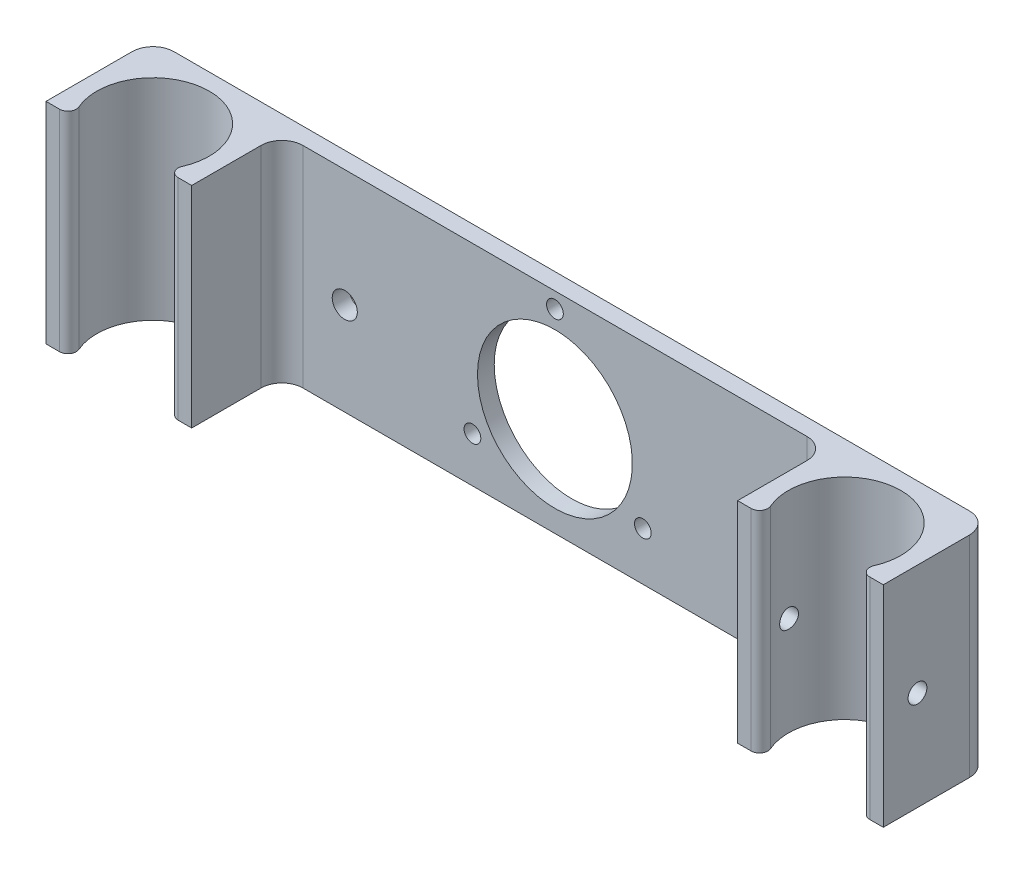
SolidWorks part; units mm, degrees
ref_plane "Front Plane" through (0, 0, 0) normal (0, 0, 1) x (1, 0, 0)
ref_plane "Top Plane" through (0, 0, 0) normal (0, 1, 0) x (1, 0, 0)
ref_plane "Right Plane" through (0, 0, 0) normal (1, 0, 0) x (0, 0, -1)
sketch "Sketch1" plane through (0, 0, 0) normal (0, 1, 0) x (1, 0, 0)
  line L1 (-17.4, 17.4) -> (17.4, 17.4)
  line L2 (-17.4, 13.4) -> (-17.4, -17.4)
  line L3 (-17.4, -17.4) -> (17.4, -17.4)
  line L4 (17.4, 17.4) -> (17.4, -17.4)
  line L5 (0, -17.4) -> (0, 17.4) construction
  line L6 (-17.4, 0) -> (17.4, 0) construction
  line L7 (-17.4, 17.4) -> (-82.6, 17.4)
  line L9 (-17.4, 13.4) -> (-82.6, 13.4)
  line L10 (-82.6, 17.4) -> (-82.6, 13.4)
  circle A0 centre (0, 0) radius 13.45
  dimension "D1" = 26.9
  dimension "D2" = 34.8
  dimension "D3" = 34.8
  dimension "D4" = 65.2
  dimension "D5" = 4
extrude "Boss-Extrude2" add sketch "Sketch1" along normal blind 52 and the other way blind 1
mirror "Mirror2" about plane through (-82.6, -1, -17.4) normal (-1, 0, 0) of "Boss-Extrude2"
fillet "Fillet1" radius 3 4 edges at (17.4, 25.5, 17.4) (-17.4, 25.5, 17.4) (-182.6, 25.5, 17.4) (-147.8, 25.5, 17.4)
fillet "Fillet2" radius 5 4 edges at (17.4, 25.5, -17.4) (-17.4, 25.5, -13.4) (-182.6, 25.5, -17.4) (-147.8, 25.5, -13.4)
sketch "Sketch9" plane through (-17.4, 0, 0) normal (-1, 0, 0) x (0, 0, 1)
  line L0 (-13.45, -1) -> (13.45, -1) construction
  line L1 (-13.45, -1) -> (13.45, -1) construction
  line L3 (14.4, -1) -> (14.4, 52) construction
  line L4 (14.4, -1) -> (14.4, 52) construction
  circle A0 centre (0, 25.5) radius 2.25
  point P5 (0, -1)
  point P9 (14.4, 25.5)
  dimension "D1" = 4.5
extrude "Cut-Extrude2" cut sketch "Sketch9" against normal through all
ref_plane "Plane2" through (-82.6, 0, 0) normal (1, 0, 0) x (0, 0, -1)
sketch "Sketch11" plane through (0, -1, 0) normal (0, -1, 0) x (1, 0, 0)
  line L1 (17.4, 14.4) -> (17.4, -12.4) construction
  line L2 (17.4, 11.3563) -> (17.4, 18.3636)
  line L3 (17.4, 18.3636) -> (-17.4, 18.3636)
  line L4 (0, -4.9607) -> (0, 23.0285) construction
  line L6 (-17.4, 11.3563) -> (-17.4, 18.3636)
  line L7 (10.688, 8.1651) -> (-10.688, 8.1651)
  line L8 (10.688, 8.1651) -> (17.4, 8.1651)
  line L9 (17.4, 8.1651) -> (17.4, 11.3563)
  line L10 (-17.4, 11.3563) -> (-17.4, 8.1651)
  line L11 (-17.4, -8.4) -> (-17.4, 14.4) construction
  line L12 (-17.4, 8.1651) -> (-10.688, 8.1651)
  line L13 (-82.6, -17.4) -> (-82.6, 33.2595) construction
  line L14 (12.4, -17.4) -> (-177.6, -17.4) construction
  line L15 (-182.6, 11.3563) -> (-182.6, 18.3636)
  line L16 (-182.6, 8.1651) -> (-182.6, 11.3563)
  line L17 (-175.888, 8.1651) -> (-182.6, 8.1651)
  line L18 (-175.888, 8.1651) -> (-154.512, 8.1651)
  line L19 (-147.8, 8.1651) -> (-154.512, 8.1651)
  line L20 (-147.8, 11.3563) -> (-147.8, 8.1651)
  line L21 (-147.8, 11.3563) -> (-147.8, 18.3636)
  line L22 (-182.6, 18.3636) -> (-147.8, 18.3636)
  circle A0 centre (0, 0) radius 13.45 construction
  point P14 (0, 18.3636)
extrude "Cut-Extrude4" cut sketch "Sketch11" against normal blind 61
fillet "Fillet3" radius 2 4 edges at (-10.688, 25.5, 8.1651) (10.688, 25.5, 8.1651) (-175.888, 25.5, 8.1651) (-154.512, 25.5, 8.1651)
sketch "Sketch12" plane through (0, 0, -17.4) normal (0, 0, -1) x (-1, 0, 0)
  line L0 (82.6, 52) -> (82.6, -1) construction
  line L1 (-12.4, 52) -> (177.6, 52) construction
  line L2 (-12.4, -1) -> (177.6, -1) construction
  circle A0 centre (82.6, 25.5) radius 18.5
  circle A1 centre (82.6, 25.5) radius 27 construction
  circle A2 centre (82.6, 48.25) radius 2
  circle A3 centre (82.6, 25.5) radius 22.75 construction
  circle A4 centre (102.3021, 12.625) radius 2
  circle A5 centre (61.5989, 13.375) radius 2
  point P19 (82.167, 24.75)
  dimension "D1" = 37
  dimension "D2" = 54
  dimension "D3" = 4
  dimension "D4" = 22.75
  dimension "D5" = 3
extrude "Cut-Extrude5" cut sketch "Sketch12" against normal blind 61
sketch "Sketch13" plane through (0, 0, -17.4) normal (0, 0, -1) x (-1, 0, 0)
  line L0 (142.8, 52) -> (142.8, -1) construction
  line L1 (22.4, -1) -> (22.4, 52) construction
  circle A0 centre (132.8, 24) radius 3
  circle A1 centre (32.4, 24) radius 3
  dimension "D1" = 6
  dimension "D3" = 6
  dimension "D2" = 10
  dimension "D4" = 10
extrude "Cut-Extrude8" cut sketch "Sketch13" against normal blind 41
sketch "Sketch14" plane through (0, 0, -17.4) normal (0, 0, -1) x (-1, 0, 0)
  line L0 (186.7057, 1.8163) -> (-25.1056, 1.8163)
  line L1 (-25.1056, 1.8163) -> (-25.1056, -12.0224)
  line L2 (-25.1056, -12.0224) -> (186.7057, -12.0224)
  line L3 (186.7057, -12.0224) -> (186.7057, 1.8163)
extrude "Cut-Extrude10" cut sketch "Sketch14" against normal blind 41 contours L2 L3 L0 L1
